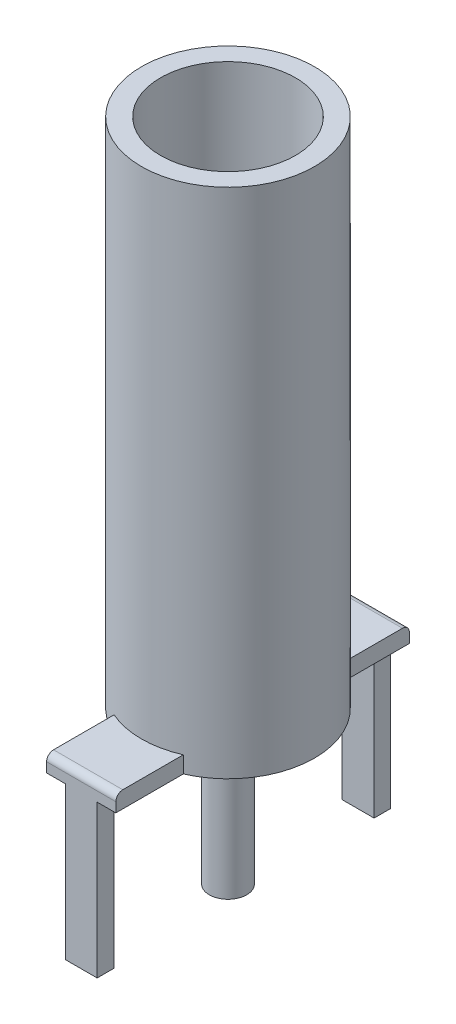
SolidWorks part; units mm, degrees
material "Brass"
ref_plane "Front Plane" through (0, 0, 0) normal (0, 0, 1) x (1, 0, 0)
ref_plane "Top Plane" through (0, 0, 0) normal (0, 1, 0) x (1, 0, 0)
ref_plane "Right Plane" through (0, 0, 0) normal (1, 0, 0) x (0, 0, -1)
sketch "Sketch1" plane through (0, 0, 0) normal (0, 1, 0) x (1, 0, 0)
  circle A0 centre (0, 0) radius 1.5875
  dimension "D1" = 3.175
extrude "Boss-Extrude1" add sketch "Sketch1" along normal blind 9.398
sketch "Sketch2" plane through (0, 0, 0) normal (0, -1, 0) x (-1, 0, 0)
  circle A0 centre (0, 0) radius 0.3429
  dimension "D1" = 0.6858
extrude "Boss-Extrude2" add sketch "Sketch2" along normal blind 2.794
sketch "Sketch3" plane through (0, 0, 0) normal (0, -1, 0) x (-1, 0, 0)
  line L0 (0, -1.5875) -> (0, 1.5875) construction
  line L1 (0.635, -2.6924) -> (-0.635, -2.6924)
  line L2 (0.635, -2.6924) -> (0.635, 2.6924)
  line L3 (0.635, 2.6924) -> (-0.635, 2.6924)
  line L4 (-0.635, -2.6924) -> (-0.635, 2.6924)
  line L5 (1.5875, 0) -> (-1.5875, 0) construction
  circle A0 centre (0, 0) radius 1.5875 construction
  dimension "D1" = 1.27
  dimension "D2" = 0.635
  dimension "D3" = 5.3848
  dimension "D4" = 2.6924
extrude "Boss-Extrude3" add sketch "Sketch3" against normal blind 0.3048
sketch "Sketch4" plane through (0, 0, 0) normal (0, -1, 0) x (-1, 0, 0)
  line L0 (0, -2.6924) -> (0, 2.6924) construction
  line L1 (0.2921, 2.3876) -> (-0.2921, 2.3876)
  line L2 (0.2921, 2.3876) -> (0.2921, 2.6924)
  line L3 (0.2921, 2.6924) -> (-0.2921, 2.6924)
  line L4 (-0.2921, 2.3876) -> (-0.2921, 2.6924)
  line L5 (-0.635, -2.6924) -> (0.635, -2.6924) construction
  line L6 (0.635, 2.6924) -> (-0.635, 2.6924) construction
  line L7 (0.2921, -2.54) -> (-0.2921, -2.54) construction
  line L8 (0.2921, -2.3876) -> (-0.2921, -2.3876)
  line L9 (0.2921, -2.3876) -> (0.2921, -2.6924)
  line L10 (0.2921, -2.6924) -> (-0.2921, -2.6924)
  line L11 (-0.2921, -2.3876) -> (-0.2921, -2.6924)
  line L12 (0.2921, 2.54) -> (-0.2921, 2.54) construction
  line L13 (1.5875, 0) -> (-1.5875, 0) construction
  arc A0 (0.635, -1.455) -> (0.635, 1.455) centre (0, 0) ccw construction
  arc A1 (-0.635, 1.455) -> (-0.635, -1.455) centre (0, 0) ccw construction
  point P10 (-0.2921, 2.54)
  point P15 (0.2921, 2.54)
  point P16 (0.2921, -2.54)
  dimension "D1" = 0.5842
  dimension "D2" = 0.3048
  dimension "D3" = 0.2921
  dimension "D4" = 5.08
  dimension "D5" = 2.54
extrude "Boss-Extrude4" add sketch "Sketch4" along normal blind 2.794
fillet "Fillet1" radius 0.127 2 edges at (0, 0.3048, -2.6924) (0, 0.3048, 2.6924)
sketch "Sketch5" plane through (0, 9.398, 0) normal (0, 1, 0) x (1, 0, 0)
  circle A0 centre (0, 0) radius 1.2371
extrude "Cut-Extrude1" cut sketch "Sketch5" against normal blind 7.874
